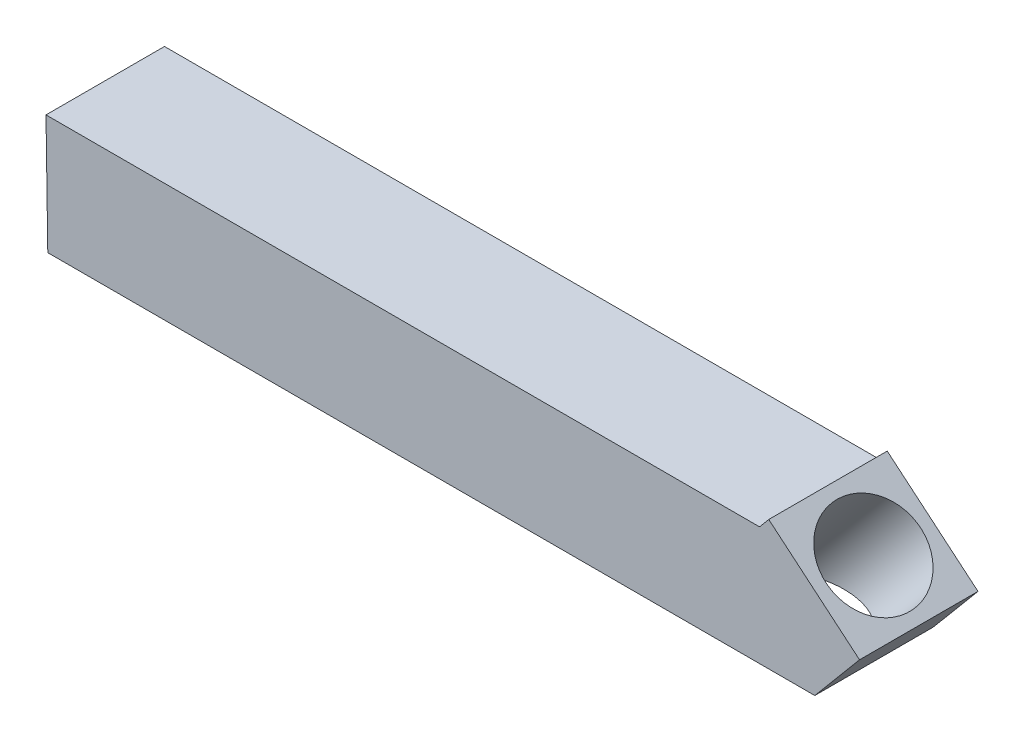
SolidWorks part; units mm, degrees
ref_plane "Front Plane" through (0, 0, 0) normal (0, 0, 1) x (1, 0, 0)
ref_plane "Top Plane" through (0, 0, 0) normal (0, 1, 0) x (1, 0, 0)
ref_plane "Right Plane" through (0, 0, 0) normal (1, 0, 0) x (0, 0, -1)
sketch "Sketch1" plane through (0, 0, 0) normal (0, 0, 1) x (1, 0, 0)
  line L0 (-70.4062, -77.7101) -> (-55.3505, -77.7101)
  line L1 (-55.3505, -77.7101) -> (-55.1558, -77.478)
  line L2 (-70.4062, -77.7101) -> (-70.3683, -80.2098)
  line L3 (-70.3683, -80.2098) -> (-54.1845, -80.2098)
  line L4 (-54.1845, -80.2098) -> (-53.2406, -79.0849)
  line L5 (-53.2406, -79.0849) -> (-55.1558, -77.478)
  line L6 (11.1852, 4.1139) -> (9.5873, 2.2096) construction
  line L7 (11.1852, 4.1139) -> (11.1852, 7.0792) construction
  line L8 (-70.4062, -77.7101) -> (-70.3683, -80.2098) construction
  ellipse E0 centre (11.2008, 4.132) end of major axis (10.4443, 4.786) minor radius 0.024 construction
  dimension "D4" = 2.5
  dimension "D5" = 2.5
  dimension "D6" = 2.4858
  dimension "D7" = 140
extrude "Boss-Extrude1" add sketch "Sketch1" along normal blind 2.5
sketch "Sketch2" plane through (-60.9395, -72.6249, 0) normal (0.6428, 0.766, 0) x (0, 0, -1)
  line L0 (-2.5, -10.0501) -> (-2.5, -7.5501) construction
  circle A0 centre (-1.25, -8.8001) radius 1
  point P4 (-2.5, -8.8001)
  dimension "D1" = 2
extrude "Cut-Extrude1" cut sketch "Sketch2" against normal blind 4.5
sketch "Sketch3" plane through (-71.5657, -1.0829, 0) normal (-0.9999, -0.0151, 0) x (0, 0, 1)
  line L0 (0, -76.6359) -> (0, -79.1359) construction
  line L1 (2.5, -79.1359) -> (0, -79.1359) construction
  circle A0 centre (1.25, -77.8859) radius 1
  point P4 (0, -77.8859)
  point P7 (1.25, -79.1359)
  dimension "D1" = 2
extrude "Cut-Extrude2" cut sketch "Sketch3" against normal blind 9.5
sketch "Sketch4" plane through (0, 0, 2.5) normal (0, 0, 1) x (1, 0, 0)
  line L0 (-70.3683, -80.2098) -> (-87.569, -80.1665)
  line L1 (-70.4062, -77.7101) -> (-70.3683, -80.2098) construction
  line L2 (-70.3683, -80.2098) -> (-54.1845, -80.2098) construction
sketch "Sketch5" plane through (-71.5657, -1.0829, 0) normal (-0.9999, -0.0151, 0) x (0, 0, 1)
  line L0 (0, -77.8859) -> (2.5, -77.8859) construction
  line L1 (0, -76.6359) -> (0, -79.1359) construction
  line L2 (2.5, -76.6359) -> (2.5, -79.1359) construction
  line L3 (1.25, -76.6359) -> (1.25, -79.1359) construction
  line L4 (2.5, -76.6359) -> (0, -76.6359) construction
  line L5 (2.5, -79.1359) -> (0, -79.1359) construction
  circle A0 centre (1.25, -77.8859) radius 1
extrude "Boss-Extrude2" add sketch "Sketch5" against normal blind 9.5
sketch "Sketch6" plane through (-71.5657, -1.0829, 0) normal (-0.9999, -0.0151, 0) x (0, 0, 1)
  line L0 (0, -76.6359) -> (2.5, -76.6359)
  line L1 (0, -76.6359) -> (0, -79.1359)
  line L2 (2.5, -76.6359) -> (2.5, -79.1359)
  line L3 (0, -79.1359) -> (2.5, -79.1359)
  line L4 (2.5, -79.1359) -> (0, -79.1359) construction
  dimension "D1" = 0
